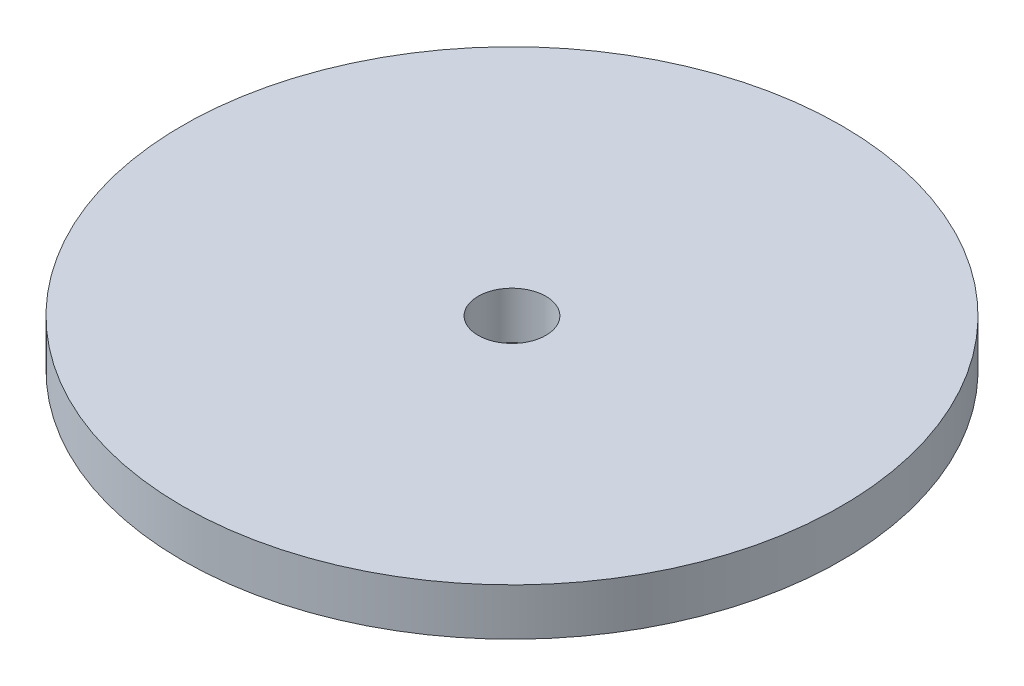
SolidWorks part; units mm, degrees
material "Maple"
ref_plane "Front Plane" through (0, 0, 0) normal (0, 0, 1) x (1, 0, 0)
ref_plane "Top Plane" through (0, 0, 0) normal (0, 1, 0) x (1, 0, 0)
ref_plane "Right Plane" through (0, 0, 0) normal (1, 0, 0) x (0, 0, -1)
sketch "Sketch1" plane through (0, 0, 0) normal (0, 1, 0) x (1, 0, 0)
  circle A0 centre (0, 0) radius 4.572
  circle A1 centre (0, 0) radius 44.45
  dimension "D1" = 9.144
  dimension "D2" = 88.9
extrude "Boss-Extrude1" add sketch "Sketch1" along normal blind 6.35
